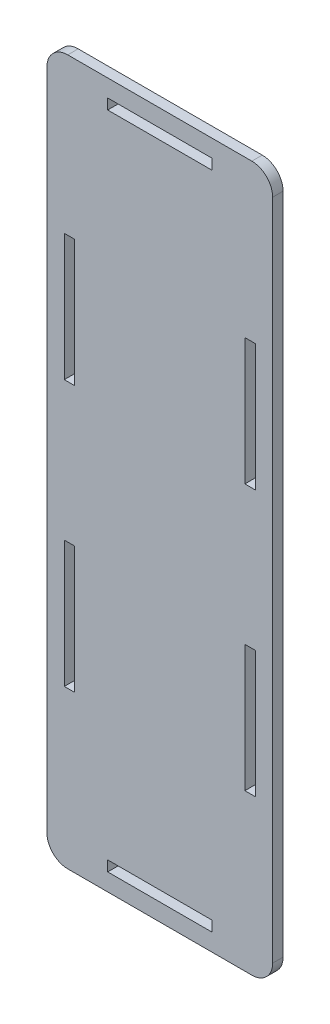
SolidWorks part; units mm, degrees
ref_plane "Front Plane" through (0, 0, 0) normal (0, 0, 1) x (1, 0, 0)
ref_plane "Top Plane" through (0, 0, 0) normal (0, 1, 0) x (1, 0, 0)
ref_plane "Right Plane" through (0, 0, 0) normal (1, 0, 0) x (0, 0, -1)
sketch "Sketch1" plane through (0, 0, 0) normal (0, 0, 1) x (1, 0, 0)
  line L1 (-26.5, 101.5) -> (26.5, 101.5)
  line L2 (-32.5, 95.5) -> (-32.5, -95.5)
  line L3 (-26.5, -101.5) -> (26.5, -101.5)
  line L4 (32.5, 95.5) -> (32.5, -95.5)
  line L5 (-32.5, 101.5) -> (32.5, -101.5) construction
  line L6 (-32.5, -101.5) -> (32.5, 101.5) construction
  arc A0 (-26.5, -101.5) -> (-32.5, -95.5) centre (-26.5, -95.5) cw
  arc A1 (26.5, -101.5) -> (32.5, -95.5) centre (26.5, -95.5) ccw
  arc A2 (26.5, 101.5) -> (32.5, 95.5) centre (26.5, 95.5) cw
  arc A3 (-26.5, 101.5) -> (-32.5, 95.5) centre (-26.5, 95.5) ccw
  point P0 (0, 0)
  dimension "D3" = 6
  dimension "D1" = 65
  dimension "D2" = 203
extrude "Boss-Extrude1" add sketch "Sketch1" along normal blind 3
sketch "Sketch2" plane through (0, 0, 3) normal (0, 0, 1) x (1, 0, 0)
  line L0 (-27.5, 0) -> (27.5, 0) construction
  line L1 (-27.5, 96.5) -> (27.5, 96.5)
  line L2 (-27.5, 96.5) -> (-27.5, -96.5)
  line L3 (-27.5, -96.5) -> (27.5, -96.5)
  line L4 (27.5, 96.5) -> (27.5, -96.5)
  line L5 (-27.5, 96.5) -> (27.5, -96.5) construction
  line L6 (-27.5, -96.5) -> (27.5, 96.5) construction
  line L11 (-15, -96.5) -> (15, -96.5)
  line L12 (-15, 93.5) -> (15, 93.5)
  line L17 (24.5, 56.5) -> (27.5, 56.5)
  line L18 (24.5, 56.5) -> (24.5, 20)
  line L19 (24.5, 20) -> (27.5, 20)
  line L20 (27.5, 56.5) -> (27.5, 20)
  line L21 (24.5, 56.5) -> (27.5, 20) construction
  line L22 (24.5, 20) -> (27.5, 56.5) construction
  line L23 (0, -96.5) -> (0, 96.5) construction
  line L24 (-15, 93.5) -> (-15, 96.5)
  line L25 (-15, 96.5) -> (15, 96.5)
  line L26 (15, 93.5) -> (15, 96.5)
  line L27 (-15, 93.5) -> (15, 96.5) construction
  line L28 (-15, 96.5) -> (15, 93.5) construction
  line L29 (15, -93.5) -> (15, -96.5)
  line L30 (-15, -93.5) -> (15, -93.5)
  line L31 (-15, -93.5) -> (-15, -96.5)
  line L32 (24.5, -20) -> (27.5, -20)
  line L33 (27.5, -56.5) -> (27.5, -20)
  line L34 (24.5, -56.5) -> (27.5, -56.5)
  line L35 (24.5, -56.5) -> (24.5, -20)
  line L36 (-24.5, -56.5) -> (-24.5, -20)
  line L37 (-24.5, -56.5) -> (-27.5, -56.5)
  line L38 (-27.5, -56.5) -> (-27.5, -20)
  line L39 (-24.5, -20) -> (-27.5, -20)
  line L40 (-24.5, 20) -> (-27.5, 20)
  line L41 (-27.5, 56.5) -> (-27.5, 20)
  line L42 (-24.5, 56.5) -> (-27.5, 56.5)
  line L43 (-24.5, 56.5) -> (-24.5, 20)
  point P0 (0, 0)
  point P5 (0, 95)
  point P11 (26, 38.25)
  dimension "D1" = 193
  dimension "D2" = 55
  dimension "D3" = 3
  dimension "D4" = 30
  dimension "D6" = 58.25
  dimension "D7" = 3
  dimension "D8" = 36.5
extrude "Cut-Extrude1" cut sketch "Sketch2" against normal blind 3 contours L43 L42 L2 L40 | L36 L39 L2 L37 | L30 L31 L3 L29 | L12 L26 L1 L24 | L35 L32 L33 L34 | L18 L19 L20 L17
